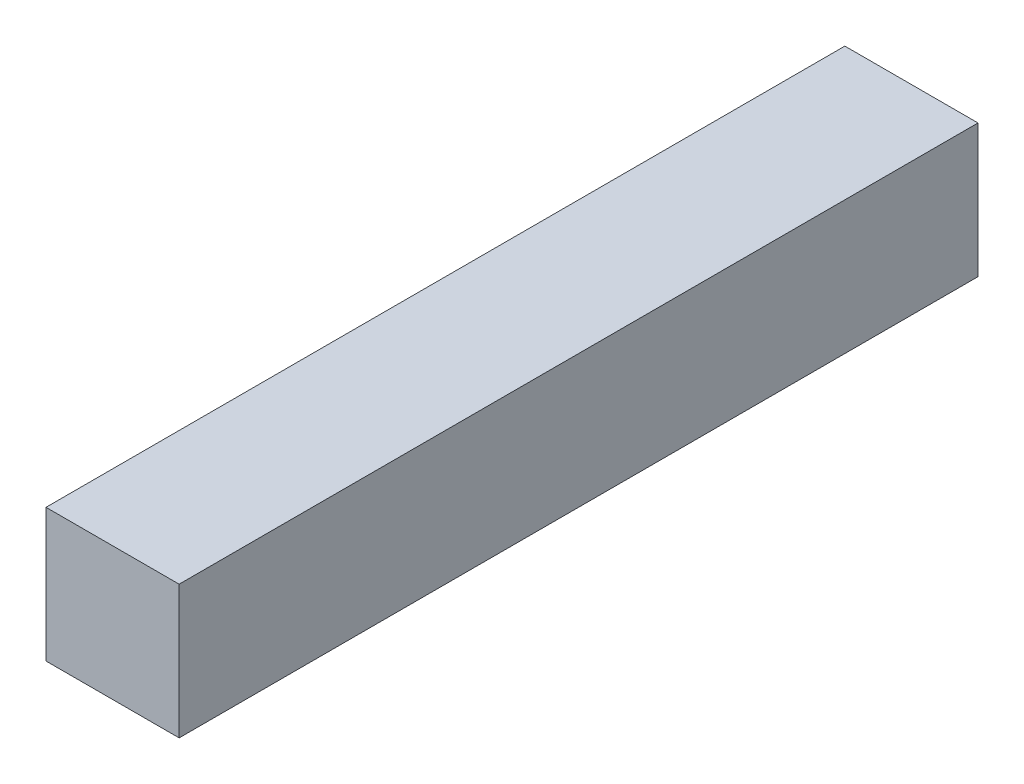
SolidWorks part; units mm, degrees
ref_plane "Front Plane" through (0, 0, 0) normal (0, 0, 1) x (1, 0, 0)
ref_plane "Top Plane" through (0, 0, 0) normal (0, 1, 0) x (1, 0, 0)
ref_plane "Right Plane" through (0, 0, 0) normal (1, 0, 0) x (0, 0, -1)
sketch "Sketch1" plane through (0, 0, 0) normal (0, 0, 1) x (1, 0, 0)
  line L1 (-5, -5) -> (5, -5)
  line L2 (-5, -5) -> (-5, 5)
  line L3 (-5, 5) -> (5, 5)
  line L4 (5, -5) -> (5, 5)
  line L5 (-5, -5) -> (5, 5) construction
  line L6 (-5, 5) -> (5, -5) construction
  dimension "D2" = 10
extrude "Boss-Extrude1" add sketch "Sketch1" along normal blind 60
sketch "Sketch3" plane through (0, 0, 0) normal (0, 0, 1) x (1, 0, 0)
  line L1 (-1.85, -2.75) -> (1.85, -2.75)
  line L2 (-1.85, -2.75) -> (-1.85, 2.75)
  line L3 (-1.85, 2.75) -> (1.85, 2.75)
  line L4 (1.85, -2.75) -> (1.85, 2.75)
  line L5 (-1.85, -2.75) -> (1.85, 2.75) construction
  line L6 (-1.85, 2.75) -> (1.85, -2.75) construction
  point P0 (0, 0)
  dimension "D1" = 3.7
  dimension "D2" = 5.5
extrude "Cut-Extrude1" cut sketch "Sketch3" along normal blind 5
